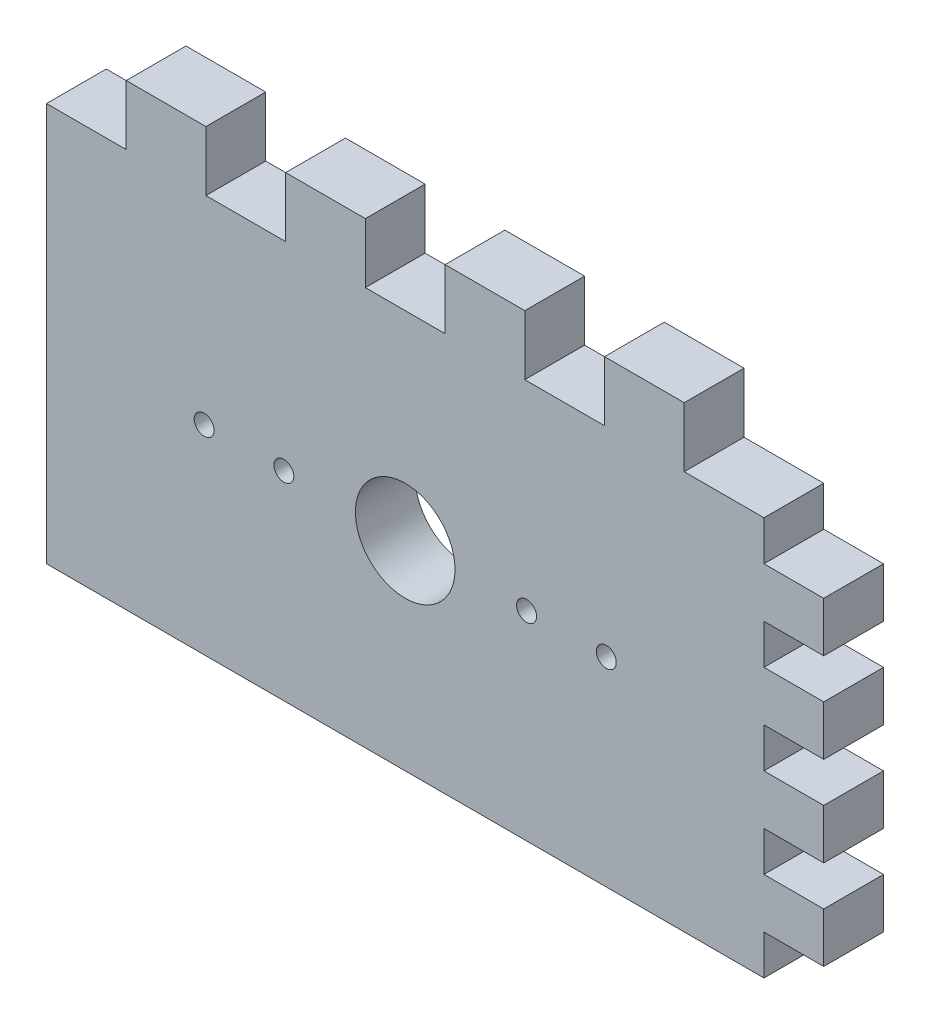
SolidWorks part; units mm, degrees
ref_plane "Front Plane" through (0, 0, 0) normal (0, 0, 1) x (1, 0, 0)
ref_plane "Top Plane" through (0, 0, 0) normal (0, 1, 0) x (1, 0, 0)
ref_plane "Right Plane" through (0, 0, 0) normal (1, 0, 0) x (0, 0, -1)
sketch "Sketch1" plane through (0, 0, 0) normal (0, 0, 1) x (1, 0, 0)
  line L0 (18, 10) -> (18, 8)
  line L1 (18, 8) -> (21, 8)
  line L2 (21, 8) -> (21, 5.5)
  line L3 (21, 5.5) -> (18, 5.5)
  line L4 (18, 5.5) -> (18, 3.5)
  line L5 (18, 3.5) -> (21, 3.5)
  line L6 (21, 3.5) -> (21, 1)
  line L7 (21, 1) -> (18, 1)
  line L8 (18, 1) -> (18, -1)
  line L9 (18, -1) -> (21, -1)
  line L10 (21, -1) -> (21, -3.5)
  line L11 (21, -3.5) -> (18, -3.5)
  line L12 (18, -3.5) -> (18, -5.5)
  line L13 (18, -5.5) -> (21, -5.5)
  line L14 (21, -5.5) -> (21, -8)
  line L15 (21, -8) -> (18, -8)
  line L16 (18, -8) -> (18, -10)
  line L17 (18, -10) -> (-18, -10)
  line L18 (-18, -10) -> (-18, 10)
  line L19 (-18, 10) -> (-14, 10)
  line L20 (-14, 10) -> (-14, 13)
  line L21 (-14, 13) -> (-10, 13)
  line L22 (-10, 13) -> (-10, 10)
  line L23 (-6, 10) -> (-6, 13)
  line L24 (-6, 13) -> (-2, 13)
  line L25 (-2, 13) -> (-2, 10)
  line L26 (2, 10) -> (2, 13)
  line L27 (2, 13) -> (6, 13)
  line L28 (6, 13) -> (6, 10)
  line L29 (10, 10) -> (10, 13)
  line L30 (10, 13) -> (14, 13)
  line L31 (14, 13) -> (14, 10)
  line L32 (-10, 10) -> (-6, 10)
  line L33 (-2, 10) -> (2, 10)
  line L34 (6, 10) -> (10, 10)
  line L35 (14, 10) -> (18, 10)
  line L36 (0, 0) -> (0, 4.2712) construction
  circle A0 centre (0, 0) radius 2.5
  circle A1 centre (-6.09, 0) radius 0.5
  circle A2 centre (-10.09, 0) radius 0.5
  circle A3 centre (10.09, 0) radius 0.5
  circle A4 centre (6.09, 0) radius 0.5
  point P36 (-18, 0)
  point P37 (0, -10)
  dimension "D4" = 5
  dimension "D7" = 6.09
  dimension "D9" = 1
  dimension "D1" = 2
  dimension "D2" = 20
  dimension "D3" = 36
  dimension "D5" = 3
  dimension "D6" = 3
  dimension "D8" = 4
extrude "Boss-Extrude1" add sketch "Sketch1" along normal blind 3
